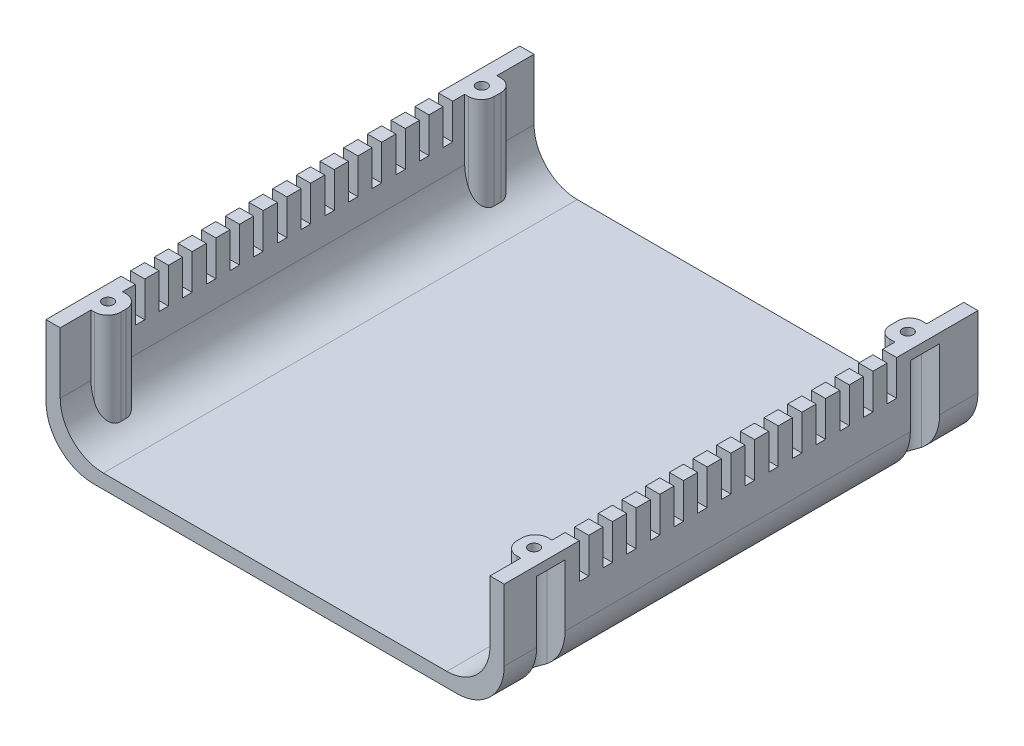
SolidWorks part; units mm, degrees
ref_plane "Front Plane" through (0, 0, 0) normal (0, 0, 1) x (1, 0, 0)
ref_plane "Top Plane" through (0, 0, 0) normal (0, 1, 0) x (1, 0, 0)
ref_plane "Right Plane" through (0, 0, 0) normal (1, 0, 0) x (0, 0, -1)
sketch "Sketch1" plane through (0, 0, 0) normal (0, 0, 1) x (1, 0, 0)
  line L0 (10, 0) -> (86.7, 0)
  line L1 (0, 25) -> (0, 10)
  line L2 (96.7, 10) -> (96.7, 25)
  line L3 (96.7, 25) -> (93.7, 25)
  line L4 (93.7, 25) -> (93.7, 12.1213)
  line L5 (84.5787, 3) -> (12.1213, 3)
  line L6 (3, 12.1213) -> (3, 25)
  line L7 (0, 25) -> (3, 25)
  arc A0 (10, 0) -> (0, 10) centre (10, 10) cw
  arc A1 (12.1213, 3) -> (3, 12.1213) centre (12.1213, 12.1213) cw
  arc A2 (93.7, 12.1213) -> (84.5787, 3) centre (84.5787, 12.1213) cw
  arc A3 (96.7, 10) -> (86.7, 0) centre (86.7, 10) cw
extrude "Boss-Extrude1" add sketch "Sketch1" along normal blind 100
sketch "Sketch2" plane through (0, 25, 0) normal (0, 1, 0) x (1, 0, 0)
  line L0 (3, -86.8385) -> (3.7201, -86.8385)
  line L1 (3, -86.8385) -> (3, -93.5085)
  line L2 (3, -93.5085) -> (3.7201, -93.5085)
  line L3 (6.5201, -89.6385) -> (6.5201, -90.7085)
  line L4 (93.7, -86.9085) -> (92.9201, -86.9085)
  line L5 (93.7, -86.9085) -> (93.7, -93.5085)
  line L6 (93.7, -93.5085) -> (92.9201, -93.5085)
  line L7 (90.1201, -89.7085) -> (90.1201, -90.7085)
  line L8 (93.7, -7.837) -> (92.6201, -7.837)
  line L9 (93.7, -7.837) -> (93.7, -14.537)
  line L10 (93.7, -14.537) -> (92.6201, -14.537)
  line L11 (90.1201, -10.337) -> (90.1201, -12.037)
  line L12 (3, -7.837) -> (3.8201, -7.837)
  line L13 (3, -7.837) -> (3, -14.637)
  line L14 (3, -14.637) -> (3.8201, -14.637)
  line L15 (6.5201, -10.537) -> (6.5201, -11.937)
  arc A0 (6.5201, -90.7085) -> (3.7201, -93.5085) centre (3.7201, -90.7085) cw
  arc A1 (6.5201, -89.6385) -> (3.7201, -86.8385) centre (3.7201, -89.6385) ccw
  arc A2 (90.1201, -90.7085) -> (92.9201, -93.5085) centre (92.9201, -90.7085) ccw
  arc A3 (90.1201, -89.7085) -> (92.9201, -86.9085) centre (92.9201, -89.7085) cw
  arc A4 (6.5201, -11.937) -> (3.8201, -14.637) centre (3.8201, -11.937) cw
  arc A5 (6.5201, -10.537) -> (3.8201, -7.837) centre (3.8201, -10.537) ccw
  arc A6 (92.6201, -14.537) -> (90.1201, -12.037) centre (92.6201, -12.037) cw
  arc A7 (92.6201, -7.837) -> (90.1201, -10.337) centre (92.6201, -10.337) ccw
  point P32 (0, 0)
  point P33 (0, 0)
  point P34 (0, 0)
  point P35 (0, 0)
  point P36 (0, 0)
  point P37 (0, 0)
  point P38 (0, 0)
  point P39 (0, 0)
  point P40 (0, 0)
  point P41 (0, 0)
  point P42 (0, 0)
  point P43 (0, 0)
  point P44 (0, 0)
  point P45 (0, 0)
  point P46 (0, 0)
  point P47 (0, 0)
  point P48 (0, 0)
  point P49 (0, 0)
  point P50 (0, 0)
  point P51 (0, 0)
  point P52 (0, 0)
  point P53 (0, 0)
  point P54 (0, 0)
  point P55 (0, 0)
  point P56 (0, 0)
  point P57 (0, 0)
  point P58 (0, 0)
  point P59 (0, 0)
  point P60 (0, 0)
  point P61 (0, 0)
  point P62 (0, 0)
  point P63 (0, 0)
  point P64 (0, 0)
  point P65 (0, 0)
extrude "Boss-Extrude2" add sketch "Sketch2" against normal blind 20
sketch "Sketch15" plane through (96.7, 0, 0) normal (1, 0, 0) x (0, 0, -1)
  line L0 (-79.1515, 29.487) -> (-79.1515, 17.5422)
  line L1 (-84.15, 29.487) -> (-82.15, 29.487)
  line L2 (-84.15, 29.487) -> (-84.15, 17.5422)
  line L3 (-84.15, 17.5422) -> (-82.15, 17.5422)
  line L4 (-82.15, 29.487) -> (-82.15, 17.5422)
  line L5 (-79.1515, 29.487) -> (-77.1515, 29.487)
  line L6 (-77.1515, 29.487) -> (-77.1515, 17.5422)
  line L7 (-79.1515, 17.5422) -> (-77.1515, 17.5422)
  line L8 (-74.1531, 29.487) -> (-74.1531, 17.5422)
  line L9 (-74.1531, 29.487) -> (-72.1531, 29.487)
  line L10 (-72.1531, 29.487) -> (-72.1531, 17.5422)
  line L11 (-74.1531, 17.5422) -> (-72.1531, 17.5422)
  line L12 (-69.1546, 29.487) -> (-69.1546, 17.5422)
  line L13 (-69.1546, 29.487) -> (-67.1546, 29.487)
  line L14 (-67.1546, 29.487) -> (-67.1546, 17.5422)
  line L15 (-69.1546, 17.5422) -> (-67.1546, 17.5422)
  line L16 (-64.1562, 29.487) -> (-64.1562, 17.5422)
  line L17 (-64.1562, 29.487) -> (-62.1562, 29.487)
  line L18 (-62.1562, 29.487) -> (-62.1562, 17.5422)
  line L19 (-64.1562, 17.5422) -> (-62.1562, 17.5422)
  line L20 (-59.1577, 29.487) -> (-59.1577, 17.5422)
  line L21 (-59.1577, 29.487) -> (-57.1577, 29.487)
  line L22 (-57.1577, 29.487) -> (-57.1577, 17.5422)
  line L23 (-59.1577, 17.5422) -> (-57.1577, 17.5422)
  line L24 (-54.1592, 29.487) -> (-54.1592, 17.5422)
  line L25 (-54.1592, 29.487) -> (-52.1592, 29.487)
  line L26 (-52.1592, 29.487) -> (-52.1592, 17.5422)
  line L27 (-54.1592, 17.5422) -> (-52.1592, 17.5422)
  line L28 (-49.1608, 29.487) -> (-49.1608, 17.5422)
  line L29 (-49.1608, 29.487) -> (-47.1608, 29.487)
  line L30 (-47.1608, 29.487) -> (-47.1608, 17.5422)
  line L31 (-49.1608, 17.5422) -> (-47.1608, 17.5422)
  line L32 (-44.1623, 29.487) -> (-44.1623, 17.5422)
  line L33 (-44.1623, 29.487) -> (-42.1623, 29.487)
  line L34 (-42.1623, 29.487) -> (-42.1623, 17.5422)
  line L35 (-44.1623, 17.5422) -> (-42.1623, 17.5422)
  line L36 (-39.1638, 29.487) -> (-39.1638, 17.5422)
  line L37 (-39.1638, 29.487) -> (-37.1638, 29.487)
  line L38 (-37.1638, 29.487) -> (-37.1638, 17.5422)
  line L39 (-39.1638, 17.5422) -> (-37.1638, 17.5422)
  line L40 (-34.1654, 29.487) -> (-34.1654, 17.5422)
  line L41 (-34.1654, 29.487) -> (-32.1654, 29.487)
  line L42 (-32.1654, 29.487) -> (-32.1654, 17.5422)
  line L43 (-34.1654, 17.5422) -> (-32.1654, 17.5422)
  line L44 (-29.1669, 29.487) -> (-29.1669, 17.5422)
  line L45 (-29.1669, 29.487) -> (-27.1669, 29.487)
  line L46 (-27.1669, 29.487) -> (-27.1669, 17.5422)
  line L47 (-29.1669, 17.5422) -> (-27.1669, 17.5422)
  line L48 (-24.1685, 29.487) -> (-24.1685, 17.5422)
  line L49 (-24.1685, 29.487) -> (-22.1685, 29.487)
  line L50 (-22.1685, 29.487) -> (-22.1685, 17.5422)
  line L51 (-24.1685, 17.5422) -> (-22.1685, 17.5422)
  line L52 (-19.17, 29.487) -> (-19.17, 17.5422)
  line L53 (-19.17, 29.487) -> (-17.17, 29.487)
  line L54 (-17.17, 29.487) -> (-17.17, 17.5422)
  line L55 (-19.17, 17.5422) -> (-17.17, 17.5422)
  line L57 (-100, 10) -> (-100, 25) construction
  line L58 (0, 10) -> (0, 25) construction
  dimension "D1" = 2
  dimension "D2" = 17.17
  dimension "D5" = 15.85
  dimension "D3" = 14
extrude "Cut-Extrude1" cut sketch "Sketch15" against normal through all both and the other way through all
sketch "Sketch16" plane through (0, 25, 0) normal (0, 1, 0) x (1, 0, 0)
  circle A0 centre (3.25, -90.15) radius 1.45 construction
  circle A1 centre (93.16, -90.15) radius 1.45 construction
  circle A2 centre (3.25, -11.2792) radius 1.45 construction
  circle A3 centre (93.16, -11.2792) radius 1.45 construction
  point P8 (0, 0)
hole_wizard "#4-40 Tapped Hole1" positions "3DSketch1" profile "Sketch17" tap size "#4-40" standard "ANSI Inch" end condition through all
sketch3d "3DSketch1"
  point P0 (3.25, 25, 11.2792)
  point P3 (3.25, 25, 90.15)
  point P6 (93.16, 25, 90.15)
  point P9 (93.16, 25, 11.2792)
sketch "Sketch17" plane through (3.25, 25, 11.2792) normal (1, 0, 0) x (0, 0, 1)
  line L0 (0, 0) -> (0, 25)
  line L1 (0, 25) -> (1.1303, 25)
  line L2 (1.1303, 25) -> (1.1303, 0)
  line L5 (1.1303, 0) -> (0, 0)
  line L11 (0, -6.35) -> (0, 107.95) construction
  dimension "Thru Tap Drill Dia." = 2.2606
  dimension "Thru Tap Drill Depth" = 25
sketch "Sketch18" plane through (0, 0, 0) normal (0, -1, 0) x (1, 0, 0)
  circle A0 centre (3.25, 90.15) radius 2.7 construction
sketch "Sketch19" plane through (0, 0, 0) normal (0, -1, 0) x (1, 0, 0)
  line L0 (3.25, 11.2792) -> (3.25, 14.2792) construction
  line L2 (3.25, 11.2792) -> (3.25, 8.2792)
  line L3 (0, 100) -> (0, 0) construction
  line L4 (0, 14.2792) -> (3.72, 14.2792)
  line L5 (0, 14.2792) -> (0, 8.2792)
  line L6 (0, 8.2792) -> (3.72, 8.2792)
  line L7 (6.22, 11.7792) -> (6.22, 10.7792)
  line L9 (96.7, 100) -> (96.7, 0) construction
  line L10 (0, 93.15) -> (3.72, 93.15)
  line L11 (0, 93.15) -> (0, 87.15)
  line L12 (0, 87.15) -> (3.72, 87.15)
  line L13 (6.22, 90.65) -> (6.22, 89.65)
  line L14 (96.7, 93.15) -> (92.92, 93.15)
  line L15 (96.7, 93.15) -> (96.7, 87.15)
  line L16 (96.7, 87.15) -> (92.92, 87.15)
  line L17 (90.42, 90.65) -> (90.42, 89.65)
  line L21 (96.7, 14.2792) -> (92.92, 14.2792)
  line L22 (96.7, 14.2792) -> (96.7, 8.1009)
  line L23 (96.7, 8.1009) -> (92.92, 8.1009)
  line L24 (90.42, 11.7792) -> (90.42, 10.6009)
  arc A0 (6.22, 11.7792) -> (3.72, 14.2792) centre (3.72, 11.7792) ccw
  arc A1 (6.22, 10.7792) -> (3.72, 8.2792) centre (3.72, 10.7792) cw
  arc A2 (6.22, 89.65) -> (3.72, 87.15) centre (3.72, 89.65) cw
  arc A3 (6.22, 90.65) -> (3.72, 93.15) centre (3.72, 90.65) ccw
  arc A4 (90.42, 89.65) -> (92.92, 87.15) centre (92.92, 89.65) ccw
  arc A5 (92.92, 93.15) -> (90.42, 90.65) centre (92.92, 90.65) ccw
  arc A6 (90.42, 11.7792) -> (92.92, 14.2792) centre (92.92, 11.7792) cw
  arc A7 (92.92, 8.1009) -> (90.42, 10.6009) centre (92.92, 10.6009) cw
  dimension "D1" = 2.5
  dimension "D2" = 2.5
  dimension "D3" = 2.5
  dimension "D4" = 2.5
  dimension "D5" = 2.5
  dimension "D6" = 2.5
  dimension "D7" = 2.5
  dimension "D8" = 2.5
extrude "Cut-Extrude2" cut sketch "Sketch19" against normal blind 23 contours L11 L12 A2 L13 A3 L10 | L5 L6 A1 L7 A0 L4 | L23 A7 L24 A6 L21 L22 | L16 A4 L17 A5 L14 L15
